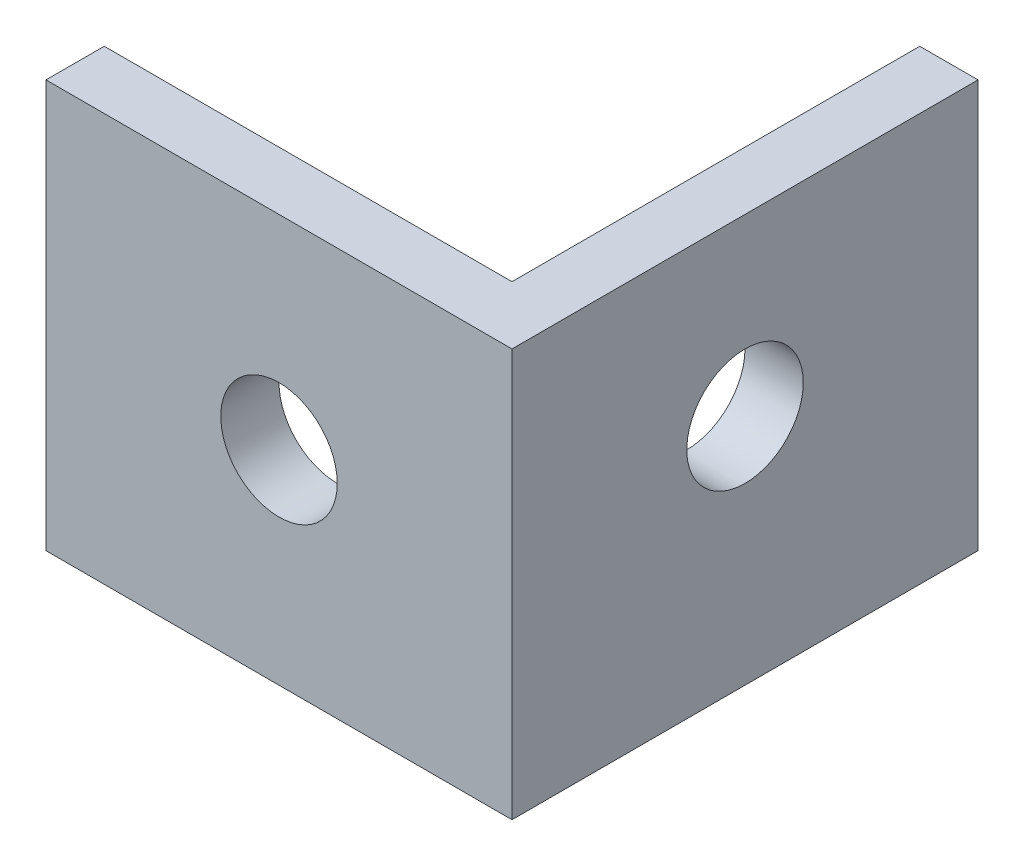
SolidWorks part; units mm, degrees
ref_plane "Front Plane" through (0, 0, 0) normal (0, 0, 1) x (1, 0, 0)
ref_plane "Top Plane" through (0, 0, 0) normal (0, 1, 0) x (1, 0, 0)
ref_plane "Right Plane" through (0, 0, 0) normal (1, 0, 0) x (0, 0, -1)
sketch "Sketch1" plane through (0, 0, 0) normal (0, 1, 0) x (1, 0, 0)
  line L0 (0, 0) -> (25.4, 0)
  line L1 (25.4, 0) -> (25.4, 25.4)
  line L2 (25.4, 25.4) -> (22.225, 25.4)
  line L3 (22.225, 25.4) -> (22.225, 3.175)
  line L4 (22.225, 3.175) -> (0, 3.175)
  line L5 (0, 3.175) -> (0, 0)
  dimension "D1" = 3.175
  dimension "D2" = 3.175
  dimension "D3" = 25.4
  dimension "D4" = 25.4
extrude "Boss-Extrude1" add sketch "Sketch1" along normal blind 22.225
sketch "Sketch2" plane through (25.4, 0, 0) normal (1, 0, 0) x (0, 0, -1)
  line L0 (0, 22.225) -> (25.4, 22.225) construction
  line L2 (0, 22.225) -> (0, 0) construction
  circle A0 centre (12.7, 12.7) radius 3.175
  dimension "D3" = 6.35
  dimension "D2" = 9.525
  dimension "D1" = 12.7
extrude "Cut-Extrude1" cut sketch "Sketch2" against normal blind 25.4
sketch "Sketch3" plane through (0, 0, 0) normal (0, 0, 1) x (1, 0, 0)
  line L0 (0, 22.225) -> (0, 0) construction
  line L1 (0, 0) -> (25.4, 0) construction
  circle A0 centre (12.7, 11.1125) radius 3.175
  dimension "D3" = 6.35
  dimension "D1" = 12.7
  dimension "D2" = 11.1125
extrude "Cut-Extrude2" cut sketch "Sketch3" against normal blind 25.4
